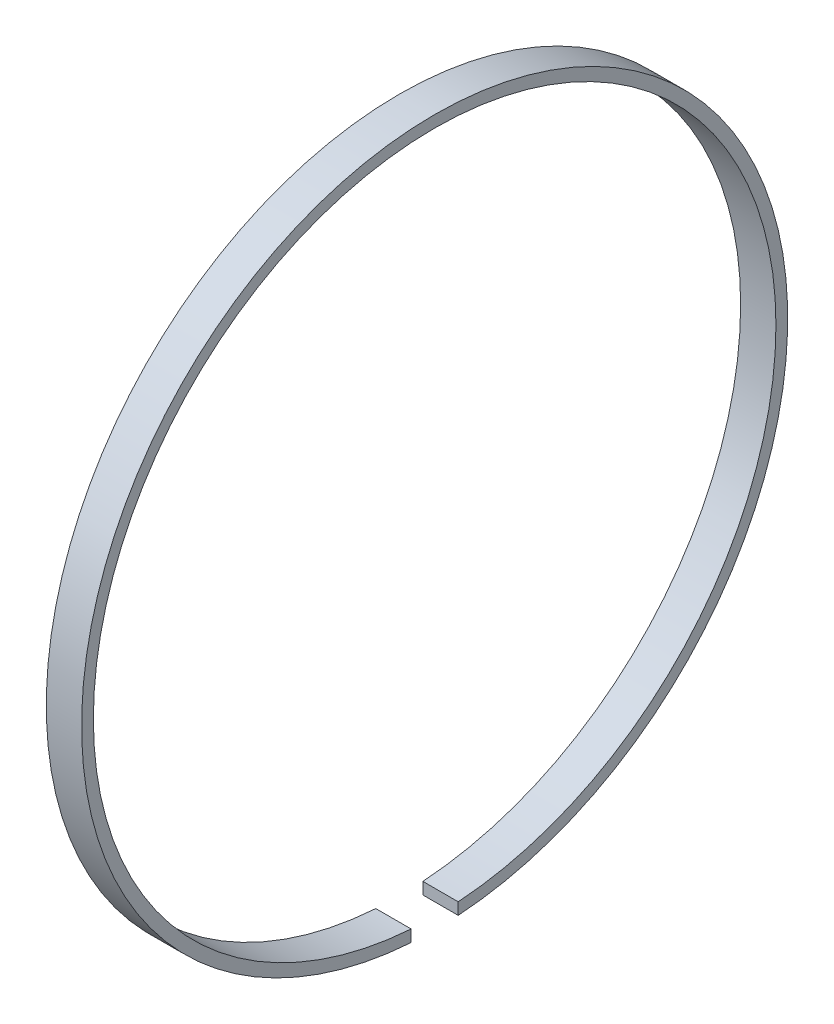
SolidWorks part; units mm, degrees
ref_plane "Front Plane" through (0, 0, 0) normal (0, 0, 1) x (1, 0, 0)
ref_plane "Top Plane" through (0, 0, 0) normal (0, 1, 0) x (1, 0, 0)
ref_plane "Right Plane" through (0, 0, 0) normal (1, 0, 0) x (0, 0, -1)
sketch "Sketch2" plane through (0, 0, 0) normal (1, 0, 0) x (0, 0, -1)
  line L0 (0, 0) -> (0, -17.2135) construction
  line L1 (-1, -14.4655) -> (-1, -14.9666)
  line L2 (1, -14.4655) -> (1, -14.9666)
  line L4 (1, 0) -> (1, -17.2135) construction
  line L5 (-1, 0) -> (-1, -17.2135) construction
  arc A0 (1, -14.9666) -> (-1, -14.9666) centre (0, 0) ccw
  arc A1 (1, -14.4655) -> (-1, -14.4655) centre (0, 0) ccw
  dimension "D1" = 29
  dimension "D2" = 0.5
  dimension "D3" = 1
  dimension "D4" = 1
extrude "Boss-Extrude1" add sketch "Sketch2" along normal blind 1.5
